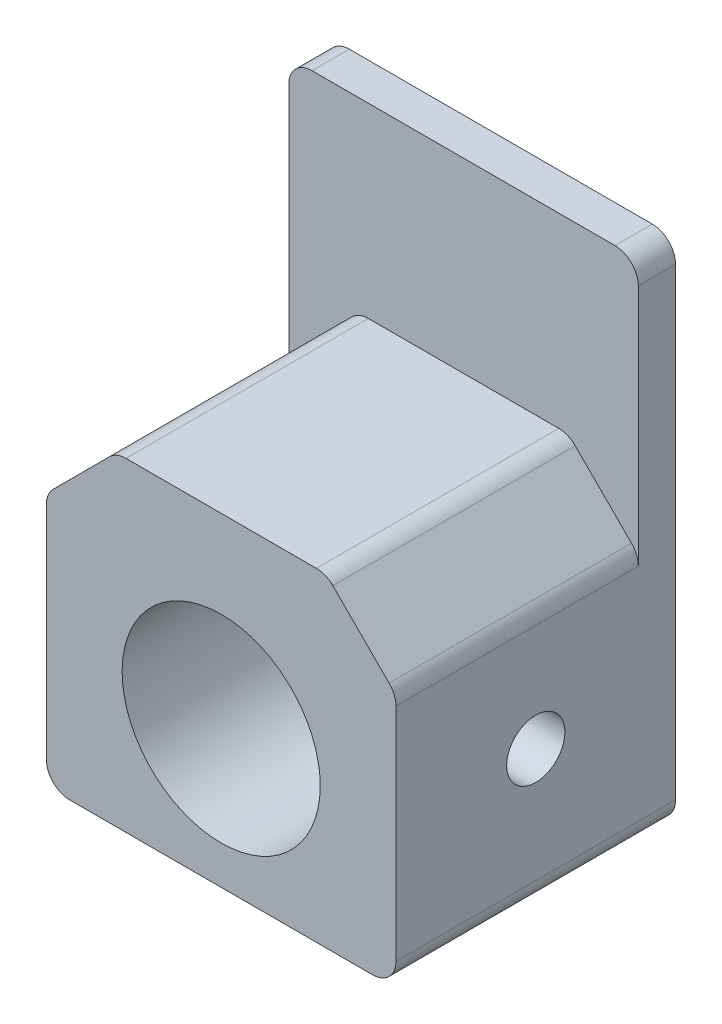
SolidWorks part; units mm, degrees
ref_plane "XY" through (0, 0, 0) normal (0, 0, 1) x (1, 0, 0)
ref_plane "XZ" through (0, 0, 0) normal (0, 1, 0) x (1, 0, 0)
ref_plane "YZ" through (0, 0, 0) normal (1, 0, 0) x (0, 0, -1)
sketch "Sketch1" plane through (0, 0, 0) normal (0, 0, 1) x (1, 0, 0)
  line L1 (6.5, 10.95) -> (-6.5, 10.95)
  line L2 (7.5, 9.95) -> (7.5, -9.95)
  line L3 (6.5, -10.95) -> (-6.5, -10.95)
  line L4 (-7.5, 9.95) -> (-7.5, -9.95)
  line L5 (7.5, 10.95) -> (-7.5, -10.95) construction
  line L6 (7.5, -10.95) -> (-7.5, 10.95) construction
  circle A0 centre (0, -5.05) radius 4.25
  arc A1 (-7.5, -9.95) -> (-6.5, -10.95) centre (-6.5, -9.95) ccw
  arc A2 (6.5, -10.95) -> (7.5, -9.95) centre (6.5, -9.95) ccw
  arc A3 (7.5, 9.95) -> (6.5, 10.95) centre (6.5, 9.95) ccw
  arc A4 (-6.5, 10.95) -> (-7.5, 9.95) centre (-6.5, 9.95) ccw
  point P0 (0, 0)
  dimension "D3" = 8.5
  dimension "D5" = 1
  dimension "D1" = 15
  dimension "D2" = 21.9
  dimension "D4" = 5.9
extrude "Boss-Extrude1" add sketch "Sketch1" along normal blind 1.6
sketch "Sketch2" plane through (0, 0, 1.6) normal (0, 0, 1) x (1, 0, 0)
  line L0 (-4.5, 2.95) -> (4.5, 2.95)
  line L1 (-4.5, 2.95) -> (-7.5, -0.05)
  line L2 (4.5, 2.95) -> (7.5, -0.05)
  line L4 (-6.5, -10.95) -> (6.5, -10.95)
  line L5 (7.5, -9.95) -> (7.5, 9.95)
  line L6 (6.5, 10.95) -> (-6.5, 10.95)
  line L7 (-7.5, 9.95) -> (-7.5, -9.95)
  line L8 (-6.5, -10.95) -> (6.5, -10.95)
  line L9 (7.5, -9.95) -> (7.5, -0.05)
  line L11 (-7.5, -0.05) -> (-7.5, -9.95)
  circle A0 centre (0, -5.05) radius 4.25 construction
  circle A1 centre (0, -5.05) radius 4.25
  arc A6 (-7.5, -9.95) -> (-6.5, -10.95) centre (-6.5, -9.95) ccw
  arc A7 (6.5, -10.95) -> (7.5, -9.95) centre (6.5, -9.95) ccw
  arc A8 (7.5, 9.95) -> (6.5, 10.95) centre (6.5, 9.95) ccw
  arc A9 (-6.5, 10.95) -> (-7.5, 9.95) centre (-6.5, 9.95) ccw
  arc A10 (-7.5, -9.95) -> (-6.5, -10.95) centre (-6.5, -9.95) ccw
  arc A11 (6.5, -10.95) -> (7.5, -9.95) centre (6.5, -9.95) ccw
  dimension "D2" = 13.9
  dimension "D3" = 135
  dimension "D4" = 135
  dimension "D5" = 3
  dimension "D6" = 3
  dimension "D1" = 0
extrude "Boss-Extrude2" add sketch "Sketch2" along normal blind 10.4
fillet "Fillet1" radius 1 4 edges at (4.5, 2.95, 6.8) (-4.5, 2.95, 6.8)
sketch "Sketch3" plane through (7.5, 0, 0) normal (1, 0, 0) x (0, 0, -1)
  line L0 (-12, -9.95) -> (-12, -0.4642) construction
  line L1 (-12, -10.95) -> (0, -10.95) construction
  circle A0 centre (-6, -5.05) radius 1.25
  point P2 (-12, -5.2071)
  dimension "D1" = 2.5
  dimension "D2" = 6
  dimension "D3" = 5.9
extrude "Cut-Extrude1" cut sketch "Sketch3" against normal through all
